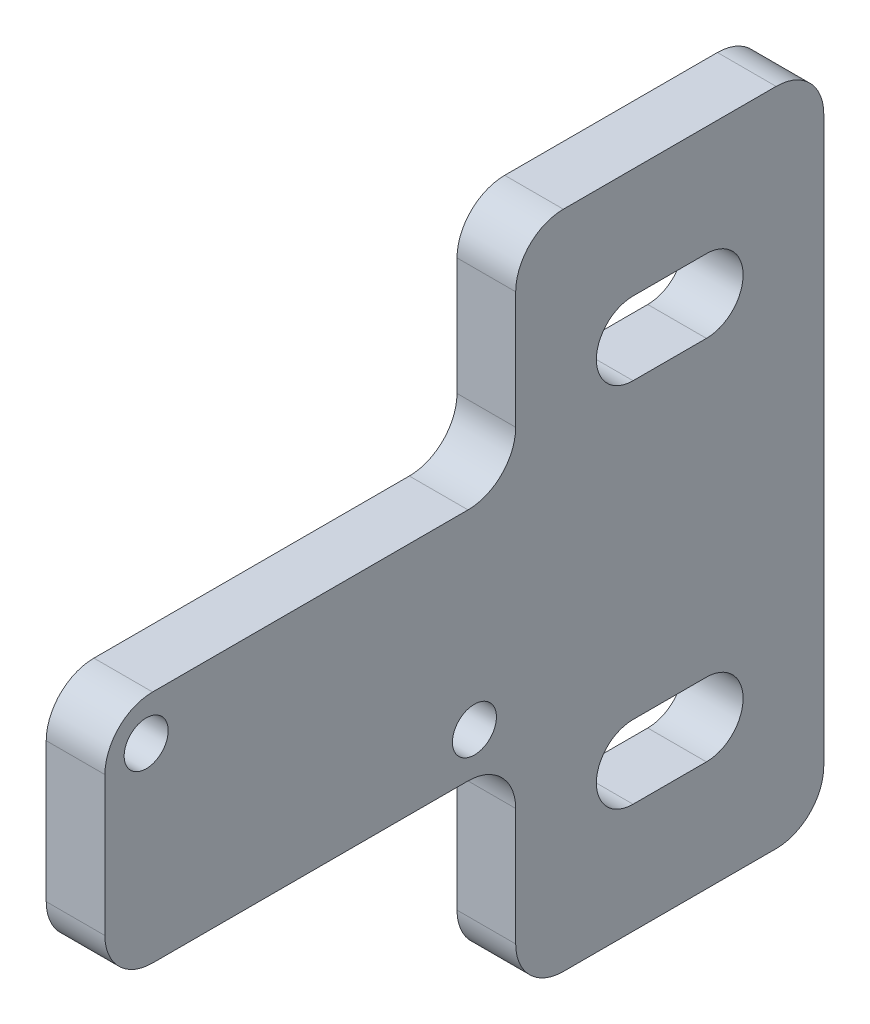
SolidWorks part; units mm, degrees
ref_plane "Front Plane" through (0, 0, 0) normal (1, 0, 0) x (0, 1, 0)
ref_plane "Top Plane" through (0, 0, 0) normal (0, 0, 1) x (0, 1, 0)
ref_plane "Right Plane" through (0, 0, 0) normal (0, 1, 0) x (-1, 0, 0)
sketch "Sketch1" plane through (0, 0, 0) normal (1, 0, 0) x (0, 1, 0)
  line L0 (-4.5, -8) -> (-4.5, -13) construction
  line L1 (0, 0) -> (16, 0)
  line L2 (0, 0) -> (0, 28)
  line L3 (0, 28) -> (16, 28)
  line L4 (16, 0) -> (16, 28)
  line L9 (-2, -8) -> (-2, -13)
  line L10 (-7, -8) -> (-7, -13)
  line L11 (20.5, -8) -> (20.5, -13) construction
  line L12 (23, -8) -> (23, -13)
  line L13 (18, -8) -> (18, -13)
  line L14 (-2.554, -10.5) -> (42.446, -10.5) construction
  line L15 (8, -18.3566) -> (8, 1.6434) construction
  line L16 (13.1872, 28) -> (13.1872, 25.1872) construction
  line L17 (-14.5, 0) -> (30.5, 0)
  line L18 (-14.5, 0) -> (-14.5, -21)
  line L19 (-14.5, -21) -> (30.5, -21)
  line L20 (30.5, 0) -> (30.5, -21)
  line L21 (13.1872, 25.1872) -> (16, 25.1872) construction
  line L22 (0, 2.8128) -> (2.8128, 2.8128) construction
  line L23 (2.8128, 2.8128) -> (2.8128, 0) construction
  circle A0 centre (13.1872, 25.1872) radius 1.5
  circle A1 centre (2.8128, 2.8128) radius 1.5
  arc A2 (-2, -8) -> (-7, -8) centre (-4.5, -8) ccw
  arc A3 (-7, -13) -> (-2, -13) centre (-4.5, -13) ccw
  arc A4 (23, -8) -> (18, -8) centre (20.5, -8) ccw
  arc A5 (18, -13) -> (23, -13) centre (20.5, -13) ccw
  point P14 (-4.5, -10.5)
  point P19 (20.5, -10.5)
  dimension "D3" = 3
  dimension "D9" = 10
  dimension "D1" = 16
  dimension "D2" = 28
  dimension "D6" = 24.6627
  dimension "D7" = 21
  dimension "D8" = 5
  dimension "D10" = 45
  dimension "D12" = 25
extrude "Boss-Extrude1" add sketch "Sketch1" along normal blind 4
fillet "Fillet1" radius 3.25 8 edges at (2, 0, 28) (2, 16, 0) (2, 30.5, 0) (2, 30.5, -21) (2, -14.5, -21) (2, -14.5, 0) (2, 0, 0) (2, 16, 28)
